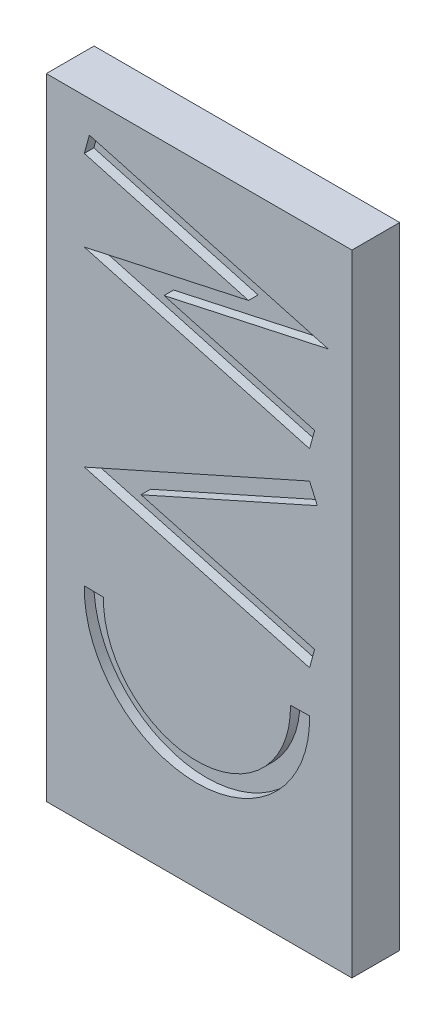
SolidWorks part; units mm, degrees
ref_plane "Front Plane" through (0, 0, 0) normal (0, 0, 1) x (1, 0, 0)
ref_plane "Top Plane" through (0, 0, 0) normal (0, 1, 0) x (1, 0, 0)
ref_plane "Right Plane" through (0, 0, 0) normal (1, 0, 0) x (0, 0, -1)
sketch "Esquisse1" plane through (0, 0, 0) normal (0, 0, 1) x (1, 0, 0)
  line L1 (16, 33) -> (-16, 33)
  line L2 (16, 33) -> (16, -33)
  line L3 (16, -33) -> (-16, -33)
  line L4 (-16, 33) -> (-16, -33)
  line L5 (16, 33) -> (-16, -33) construction
  line L6 (16, -33) -> (-16, 33) construction
  point P0 (0, 0)
  dimension "D1" = 66
  dimension "D2" = 32
extrude "Boss.-Extru.1" add sketch "Esquisse1" along normal blind 5
sketch "Esquisse2" plane through (0, 0, 5) normal (0, 0, 1) x (1, 0, 0)
  line L0 (-10.0205, -11.4847) -> (-12.0202, -11.4492)
  line L1 (9.563, -11.4847) -> (11.5627, -11.4492)
  line L2 (11.5627, -7.0922) -> (-12.0202, -0.6863)
  line L3 (-12.0202, -0.6863) -> (11.5627, 9.8375)
  line L4 (12.0869, -5.1621) -> (-6.0825, -0.2267)
  line L5 (-6.0825, -0.2267) -> (12.3777, 8.0111)
  line L6 (11.5627, -7.0922) -> (12.0869, -5.1621)
  line L7 (11.5627, 9.8375) -> (12.3777, 8.0111)
  line L8 (11.5627, 12.7659) -> (-12.0202, 19.2632)
  line L9 (-12.0202, 19.2632) -> (5.1704, 23.0152)
  line L10 (5.1704, 23.0152) -> (-12.0202, 27.7514)
  line L11 (12.0939, 14.694) -> (-3.673, 19.038)
  line L12 (-3.673, 19.038) -> (13.5177, 22.7899)
  line L13 (13.5177, 22.7899) -> (-11.489, 29.6795)
  line L14 (11.5627, 12.7659) -> (12.0939, 14.694)
  line L15 (-12.0202, 27.7514) -> (-11.489, 29.6795)
  arc A0 (-10.0205, -11.4847) -> (9.563, -11.4847) centre (-0.2288, -11.6588) ccw
  arc A1 (-12.0202, -11.4492) -> (11.5627, -11.4492) centre (-0.2288, -11.6588) ccw
  dimension "D1" = 2
  dimension "D2" = 2
  dimension "D3" = 2
extrude "Enlèv. mat.-Extru.1" cut sketch "Esquisse2" against normal blind 1
